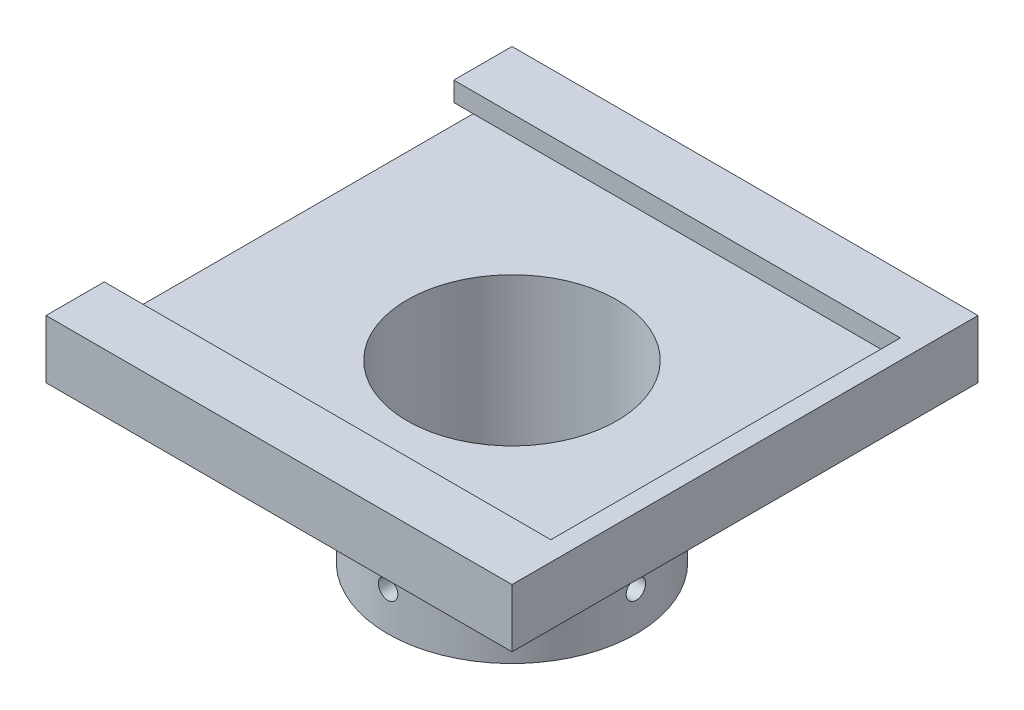
SolidWorks part; units mm, degrees
material "AISI 316 Stainless Steel Sheet (SS)"
ref_plane "Front Plane" through (0, 0, 0) normal (0, 0, 1) x (1, 0, 0)
ref_plane "Top Plane" through (0, 0, 0) normal (0, 1, 0) x (1, 0, 0)
ref_plane "Right Plane" through (0, 0, 0) normal (1, 0, 0) x (0, 0, -1)
sketch "Sketch1" plane through (0, 0, 0) normal (0, 1, 0) x (1, 0, 0)
  circle A0 centre (0, 0) radius 17.145
  circle A1 centre (0, 0) radius 20.32
  dimension "D1" = 34.29
  dimension "D2" = 40.64
extrude "Boss-Extrude1" add sketch "Sketch1" along normal blind 25.4
sketch "Sketch2" plane through (0, 25.4, 0) normal (0, 1, 0) x (1, 0, 0)
  line L1 (-38.1, 38.1) -> (38.1, 38.1)
  line L2 (-38.1, 38.1) -> (-38.1, -38.1)
  line L3 (-38.1, -38.1) -> (38.1, -38.1)
  line L4 (38.1, 38.1) -> (38.1, -38.1)
  circle A0 centre (0, 0) radius 17.145
  dimension "D1" = 76.2
  dimension "D2" = 76.2
  dimension "D3" = 38.1
  dimension "D4" = 38.1
extrude "Boss-Extrude2" add sketch "Sketch2" along normal blind 3.175
sketch "Sketch3" plane through (0, 28.575, 0) normal (0, 1, 0) x (1, 0, 0)
  line L0 (38.1, -38.1) -> (38.1, 38.1) construction
  line L1 (-38.1, 38.1) -> (38.1, 38.1)
  line L2 (-38.1, 38.1) -> (-38.1, 34.925)
  line L3 (-38.1, 34.925) -> (38.1, 34.925)
  line L4 (38.1, 38.1) -> (38.1, 34.925)
  line L6 (-38.1, -38.1) -> (38.1, -38.1)
  line L7 (-38.1, -38.1) -> (-38.1, -34.925)
  line L8 (-38.1, -34.925) -> (38.1, -34.925)
  line L9 (38.1, -38.1) -> (38.1, -34.925)
  dimension "D1" = 3.175
  dimension "D2" = 3.175
extrude "Boss-Extrude3" add sketch "Sketch3" along normal blind 6.35
sketch "Sketch4" plane through (0, 0, -34.925) normal (0, 0, 1) x (1, 0, 0)
  line L0 (-38.1, 28.575) -> (38.1, 28.575) construction
  line L1 (38.1, 34.925) -> (34.925, 34.925)
  line L2 (38.1, 34.925) -> (38.1, 28.575)
  line L3 (38.1, 28.575) -> (34.925, 28.575)
  line L4 (34.925, 34.925) -> (34.925, 28.575)
  dimension "D1" = 3.175
extrude "Boss-Extrude4" add sketch "Sketch4" along normal up to next
sketch "Sketch5" plane through (34.925, 0, 0) normal (-1, 0, 0) x (0, 0, 1)
  line L1 (-34.925, 34.925) -> (-28.575, 34.925)
  line L2 (-34.925, 34.925) -> (-34.925, 31.75)
  line L3 (-34.925, 31.75) -> (-28.575, 31.75)
  line L4 (-28.575, 34.925) -> (-28.575, 31.75)
  line L5 (34.925, 34.925) -> (28.575, 34.925)
  line L6 (34.925, 34.925) -> (34.925, 31.75)
  line L7 (34.925, 31.75) -> (28.575, 31.75)
  line L8 (28.575, 34.925) -> (28.575, 31.75)
  dimension "D1" = 6.35
  dimension "D2" = 6.35
  dimension "D3" = 3.175
  dimension "D4" = 3.175
extrude "Boss-Extrude5" add sketch "Sketch5" along normal up to surface (73.025 mm away) up to face at (-38.1, 31.3531, -4.3656)
sketch "Sketch7" plane through (0, 0, 0) normal (1, 0, 0) x (0, 0, -1)
  circle A0 centre (0, 6.35) radius 1.5875
  dimension "D1" = 3.175
  dimension "D2" = 6.35
extrude "Cut-Extrude1" cut sketch "Sketch7" against normal through all and the other way through all
pattern_circular "CirPattern1" count 4 over 360 about axis through (0, 25.4, 0) along (0, -1, 0) of "Cut-Extrude1"
